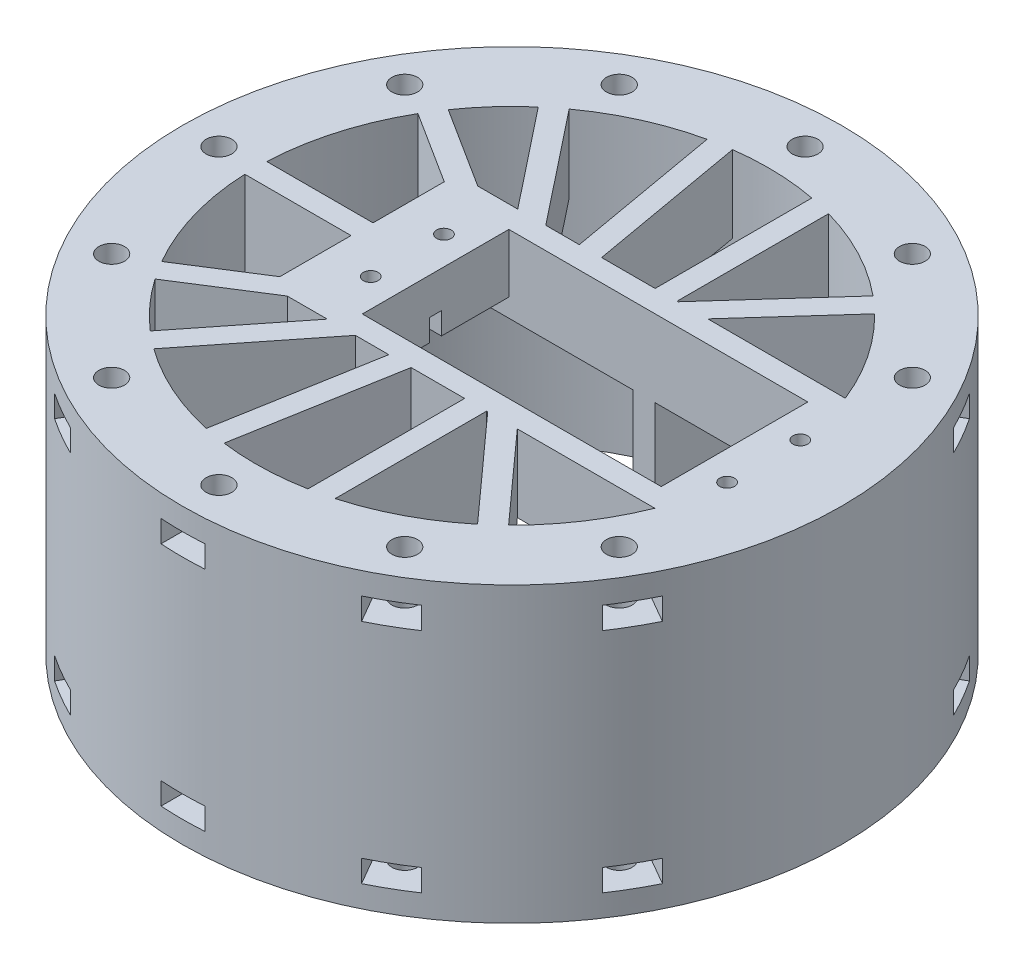
SolidWorks part; units mm, degrees
ref_plane "Front Plane" through (0, 0, 0) normal (0, 0, 1) x (1, 0, 0)
ref_plane "Top Plane" through (0, 0, 0) normal (0, 1, 0) x (1, 0, 0)
ref_plane "Right Plane" through (0, 0, 0) normal (1, 0, 0) x (0, 0, -1)
sketch "Sketch1" plane through (0, 0, 0) normal (0, 1, 0) x (1, 0, 0)
  line L0 (-43.0464, 0) -> (41.9462, 0) construction
  line L1 (0, 43.1152) -> (0, -41.8775) construction
  circle A1 centre (0, 0) radius 45
  dimension "D2" = 90
extrude "Boss-Extrude1" add sketch "Sketch1" along normal blind 40
sketch "Sketch2" plane through (0, 0, 0) normal (0, -1, 0) x (1, 0, 0)
  circle A0 centre (0, 0) radius 35
  dimension "D1" = 70
extrude "Cut-Extrude1" cut sketch "Sketch2" against normal blind 29.5
sketch "Sketch3" plane through (0, 29.5, 0) normal (0, -1, 0) x (1, 0, 0)
  line L0 (35, 0) -> (-35, 0) construction
  line L1 (0, -35) -> (0, 35) construction
  line L3 (37.5324, -10) -> (-17.4676, -10)
  line L4 (37.5324, -10) -> (37.5324, 10)
  line L5 (37.5324, 10) -> (-17.4676, 10)
  line L6 (-17.4676, -10) -> (-17.4676, 10)
  circle A0 centre (0, 0) radius 35 construction
  circle A1 centre (0, 0) radius 35 construction
  dimension "D1" = 20
  dimension "D2" = 55
  dimension "D3" = 10
  dimension "D4" = 37.5324
extrude "Cut-Extrude2" cut sketch "Sketch3" against normal blind 2.5 and the other way up to next
sketch "Sketch4" plane through (0, 32, 0) normal (0, -1, 0) x (1, 0, 0)
  line L0 (37.5324, 0) -> (-17.4676, 0) construction
  line L1 (37.5324, 10) -> (37.5324, -10) construction
  line L2 (-17.4676, 10) -> (-17.4676, -10) construction
  line L3 (0, -10) -> (0, 10) construction
  line L4 (-17.4676, -10) -> (33.541, -10) construction
  line L5 (33.541, 10) -> (-17.4676, 10) construction
  line L7 (30.3722, -10) -> (-10.4278, -10)
  line L8 (30.3722, -10) -> (30.3722, 10)
  line L9 (30.3722, 10) -> (-10.4278, 10)
  line L10 (-10.4278, -10) -> (-10.4278, 10)
  dimension "D1" = 20
  dimension "D2" = 40.8
  dimension "D3" = 30.3722
  dimension "D4" = 10
extrude "Cut-Extrude3" cut sketch "Sketch4" against normal blind 9
sketch "Sketch8" plane through (0, 29.5, 0) normal (0, -1, 0) x (1, 0, 0)
  line L0 (-17.4676, 0) -> (-35, 0) construction
  line L1 (-17.4676, 10) -> (-17.4676, -10) construction
  line L2 (8.0367, 10) -> (8.0367, 34.0648) construction
  line L3 (33.541, 10) -> (-17.4676, 10) construction
  line L4 (8.0367, -10) -> (8.0367, -29.3194) construction
  line L5 (-17.4676, -10) -> (33.541, -10) construction
  line L6 (6.5367, 10) -> (6.5367, 34.3842)
  line L7 (9.5367, 10) -> (9.5367, 33.6757)
  line L8 (9.5367, 10) -> (6.5367, 10)
  line L9 (9.5367, -10) -> (6.5367, -10)
  line L10 (6.5367, -10) -> (6.5367, -34.3842)
  line L11 (9.5367, -10) -> (9.5367, -33.6757)
  line L12 (-17.4676, 1.5) -> (-34.9678, 1.5)
  line L13 (-17.4676, -1.5) -> (-34.9678, -1.5)
  line L14 (-17.4676, 1.5) -> (-17.4676, -1.5)
  arc A0 (33.541, 10) -> (33.541, -10) centre (0, 0) ccw construction
  arc A1 (9.5367, 33.6757) -> (6.5367, 34.3842) centre (7.9531, 33.6757) ccw
  arc A2 (9.5367, -33.6757) -> (6.5367, -34.3842) centre (7.9531, -33.6757) cw
  arc A3 (-34.9678, 1.5) -> (-34.9678, -1.5) centre (-34.9678, 0) ccw
  dimension "D3" = 1.5
  dimension "D1" = 1.5
  dimension "D2" = 1.5
  dimension "D4" = 1.5
extrude "Boss-Extrude2" add sketch "Sketch8" along normal through all
sketch "Sketch16" plane through (0, 32, 0) normal (0, -1, 0) x (1, 0, 0)
  line L0 (-17.4676, 0) -> (37.5324, 0) construction
  line L1 (-17.4676, 10) -> (-17.4676, -10) construction
  line L2 (37.5324, -10) -> (37.5324, 10) construction
  line L3 (30.3722, -0.8) -> (37.5324, -0.8)
  line L4 (-10.4278, -0.8) -> (-17.4676, -0.8)
  line L5 (-10.4278, 10) -> (-10.4278, -10) construction
  line L6 (-10.4278, 0.8) -> (-17.4676, 0.8)
  line L7 (-17.4676, 0.8) -> (-17.4676, -0.8)
  line L8 (-10.4278, 0.8) -> (-10.4278, -0.8)
  line L9 (30.3722, -10) -> (30.3722, 10) construction
  line L10 (30.3722, 0.8) -> (37.5324, 0.8)
  line L11 (37.5324, 0.8) -> (37.5324, -0.8)
  line L12 (30.3722, 0.8) -> (30.3722, -0.8)
  dimension "D1" = 0.8
extrude "Cut-Extrude10" cut sketch "Sketch16" against normal blind 3
sketch "Sketch27" plane through (0, 0, 0) normal (0, -1, 0) x (1, 0, 0)
  line L0 (0, 0) -> (0, -53.17) construction
  line L1 (0, 0) -> (47.7582, -27.5732) construction
  line L3 (31.641, -18.2679) -> (31.641, -21.7321) construction
  line L4 (31.641, -21.7321) -> (34.641, -23.4641) construction
  line L5 (34.641, -23.4641) -> (37.641, -21.7321) construction
  line L6 (37.641, -21.7321) -> (37.641, -18.2679) construction
  line L7 (37.641, -18.2679) -> (34.641, -16.5359) construction
  line L8 (34.641, -16.5359) -> (31.641, -18.2679) construction
  circle A0 centre (0, 0) radius 40 construction
  circle A1 centre (34.641, -20) radius 1.75
  circle A2 centre (0, 0) radius 35 construction
  circle A3 centre (34.641, -20) radius 3 construction
  circle A4 centre (20, -34.641) radius 1.75
  circle A5 centre (0, -40) radius 1.75
  circle A6 centre (-20, -34.641) radius 1.75
  circle A7 centre (-34.641, -20) radius 1.75
  circle A8 centre (-40, 0) radius 1.75
  circle A9 centre (-34.641, 20) radius 1.75
  circle A10 centre (-20, 34.641) radius 1.75
  circle A11 centre (0, 40) radius 1.75
  circle A12 centre (20, 34.641) radius 1.75
  circle A13 centre (34.641, 20) radius 1.75
  circle A15 centre (40, 0) radius 1.75 [skipped]
  point P28 (0, 0)
  point P41 (0, 0)
  dimension "D1" = 80
  dimension "D3" = 3.5
  dimension "D4" = 70
  dimension "D5" = 6
  dimension "D6" = 12
  dimension "D2" = 60
extrude "Cut-Extrude15" cut sketch "Sketch27" against normal through all
ref_plane "Plane1" through (0, 37, 0) normal (0, 1, 0) x (1, 0, 0)
sketch "Sketch28" plane through (0, 37, 0) normal (0, 1, 0) x (1, 0, 0)
  line L0 (0, 0) -> (-54.493, 0) construction
  line L1 (-31.641, 18.2679) -> (-31.641, 21.7321)
  line L2 (-36.5359, 0) -> (-38.2679, 3)
  line L3 (-38.2679, 3) -> (-44.8999, 3)
  line L4 (-31.641, 21.7321) -> (-37.3844, 25.048)
  line L5 (-40.3844, 19.8519) -> (-34.641, 16.5359)
  line L6 (-44.8999, -3) -> (-38.2679, -3)
  line L7 (-38.2679, -3) -> (-36.5359, 0)
  line L8 (-43.4641, 0) -> (-42.5981, -1.5) [skipped]
  line L9 (-41.7321, 3) -> (-42.5981, 1.5) [skipped]
  line L10 (-34.641, 16.5359) -> (-31.641, 18.2679)
  line L11 (-18.2679, 31.641) -> (-16.5359, 34.641)
  line L12 (-16.5359, 34.641) -> (-19.8519, 40.3844)
  line L13 (-25.048, 37.3844) -> (-21.7321, 31.641)
  line L14 (-21.7321, 31.641) -> (-18.2679, 31.641)
  line L15 (0, 36.5359) -> (3, 38.2679)
  line L16 (3, 38.2679) -> (3, 44.8999)
  line L17 (-3, 44.8999) -> (-3, 38.2679)
  line L18 (-3, 38.2679) -> (0, 36.5359)
  line L19 (18.2679, 31.641) -> (21.7321, 31.641)
  line L20 (21.7321, 31.641) -> (25.048, 37.3844)
  line L21 (19.8519, 40.3844) -> (16.5359, 34.641)
  line L22 (16.5359, 34.641) -> (18.2679, 31.641)
  line L23 (31.641, 18.2679) -> (34.641, 16.5359)
  line L24 (34.641, 16.5359) -> (40.3844, 19.8519)
  line L25 (37.3844, 25.048) -> (31.641, 21.7321)
  line L26 (31.641, 21.7321) -> (31.641, 18.2679)
  line L31 (31.641, -18.2679) -> (31.641, -21.7321)
  line L32 (31.641, -21.7321) -> (37.3844, -25.048)
  line L33 (40.3844, -19.8519) -> (34.641, -16.5359)
  line L34 (34.641, -16.5359) -> (31.641, -18.2679)
  line L35 (18.2679, -31.641) -> (16.5359, -34.641)
  line L36 (16.5359, -34.641) -> (19.8519, -40.3844)
  line L37 (25.048, -37.3844) -> (21.7321, -31.641)
  line L38 (21.7321, -31.641) -> (18.2679, -31.641)
  line L39 (0, -36.5359) -> (-3, -38.2679)
  line L40 (-3, -38.2679) -> (-3, -44.8999)
  line L41 (3, -44.8999) -> (3, -38.2679)
  line L42 (3, -38.2679) -> (0, -36.5359)
  line L43 (-18.2679, -31.641) -> (-21.7321, -31.641)
  line L44 (-21.7321, -31.641) -> (-25.048, -37.3844)
  line L45 (-19.8519, -40.3844) -> (-16.5359, -34.641)
  line L46 (-16.5359, -34.641) -> (-18.2679, -31.641)
  line L47 (-31.641, -18.2679) -> (-34.641, -16.5359)
  line L48 (-34.641, -16.5359) -> (-40.3844, -19.8519)
  line L49 (-37.3844, -25.048) -> (-31.641, -21.7321)
  line L50 (-31.641, -21.7321) -> (-31.641, -18.2679)
  line L51 (36.5359, 0) -> (38.2679, -3) [skipped]
  line L52 (38.2679, -3) -> (44.8999, -3) [skipped]
  line L53 (44.8999, 3) -> (38.2679, 3) [skipped]
  line L54 (38.2679, 3) -> (36.5359, 0) [skipped]
  arc A0 (-44.8999, 3) -> (-44.8999, -3) centre (0, 0) ccw
  circle A1 centre (-40, 0) radius 3 construction
  arc A2 (-37.3844, 25.048) -> (-40.3844, 19.8519) centre (0, 0) ccw
  circle A3 centre (-34.641, 20) radius 3 construction
  arc A4 (-19.8519, 40.3844) -> (-25.048, 37.3844) centre (0, 0) ccw
  circle A5 centre (-20, 34.641) radius 3 construction
  arc A6 (3, 44.8999) -> (-3, 44.8999) centre (0, 0) ccw
  circle A7 centre (0, 40) radius 3 construction
  arc A8 (25.048, 37.3844) -> (19.8519, 40.3844) centre (0, 0) ccw
  circle A9 centre (20, 34.641) radius 3 construction
  arc A10 (40.3844, 19.8519) -> (37.3844, 25.048) centre (0, 0) ccw
  circle A11 centre (34.641, 20) radius 3 construction
  arc A14 (37.3844, -25.048) -> (40.3844, -19.8519) centre (0, 0) ccw
  circle A15 centre (34.641, -20) radius 3 construction
  arc A16 (19.8519, -40.3844) -> (25.048, -37.3844) centre (0, 0) ccw
  circle A17 centre (20, -34.641) radius 3 construction
  arc A18 (-3, -44.8999) -> (3, -44.8999) centre (0, 0) ccw
  circle A19 centre (0, -40) radius 3 construction
  arc A20 (-25.048, -37.3844) -> (-19.8519, -40.3844) centre (0, 0) ccw
  circle A21 centre (-20, -34.641) radius 3 construction
  arc A22 (-40.3844, -19.8519) -> (-37.3844, -25.048) centre (0, 0) ccw
  circle A23 centre (-34.641, -20) radius 3 construction
  arc A24 (44.8999, -3) -> (44.8999, 3) centre (0, 0) ccw [skipped]
  circle A25 centre (40, 0) radius 3 construction
  point P94 (0, 0)
  dimension "D1" = 90
  dimension "D2" = 6
  dimension "D3" = 12
extrude "Cut-Extrude17" cut sketch "Sketch28" against normal blind 3
sketch "Sketch29" plane through (0, 29.5, 0) normal (0, -1, 0) x (1, 0, 0)
  line L0 (32.4962, -13) -> (13.7255, -13)
  line L1 (9.5367, -33.6757) -> (9.5367, -10) construction
  line L2 (9.5367, -13) -> (9.5367, -33.6757)
  line L3 (9.5367, -10) -> (33.541, -10) construction
  line L4 (6.5367, -13) -> (-0.7691, -13)
  line L5 (6.5367, -10) -> (6.5367, -34.3842) construction
  line L6 (-20.4676, -11.223) -> (-20.4676, -1.5)
  line L7 (-34.9678, -1.5) -> (-17.4676, -1.5) construction
  line L8 (-20.4676, -1.5) -> (-34.9678, -1.5)
  line L9 (-17.4676, -0.8) -> (-17.4676, -10) construction
  line L10 (32.4962, 13) -> (13.7255, 13)
  line L11 (9.5367, 10) -> (9.5367, 33.6757) construction
  line L12 (9.5367, 13) -> (9.5367, 33.6757)
  line L13 (-7.5493, 34.1761) -> (-3.8154, 13)
  line L14 (6.5367, 13) -> (-0.7691, 13)
  line L15 (6.5367, 34.3842) -> (6.5367, 10) construction
  line L16 (-20.4676, 11.223) -> (-20.4676, 1.5)
  line L17 (-17.4676, 1.5) -> (-34.9678, 1.5) construction
  line L18 (-20.4676, 1.5) -> (-34.9678, 1.5)
  line L19 (6.5367, 13) -> (6.5367, 34.3842)
  line L20 (6.5367, -34.3842) -> (6.5367, -13)
  line L21 (0, 0) -> (-21.7353, -27.4331) construction
  line L22 (-20.5397, -28.3394) -> (-8.3862, -13)
  line L23 (-22.8911, -26.4764) -> (-12.2137, -13)
  line L24 (0, 0) -> (-20.4676, -13) construction
  line L25 (-17.6698, -13) -> (-28.713, -20.0141)
  line L26 (-20.4676, -11.223) -> (-30.3215, -17.4817)
  line L27 (0, 0) -> (-35, 0) construction
  line L28 (-20.4676, 11.223) -> (-30.3215, 17.4817)
  line L29 (-17.6698, 13) -> (-28.713, 20.0141)
  line L30 (-22.8911, 26.4764) -> (-12.2137, 13)
  line L31 (-20.5397, 28.3394) -> (-8.3862, 13)
  line L32 (-12.2137, 13) -> (-17.6698, 13)
  line L33 (0, 0) -> (-6.0777, -34.4683) construction
  line L34 (-4.5949, -34.6971) -> (-0.7691, -13)
  line L35 (-7.5493, -34.1761) -> (-3.8154, -13)
  line L36 (-3.8154, -13) -> (-17.6698, -13)
  line L37 (-4.5949, 34.6971) -> (-0.7691, 13)
  line L38 (-3.8154, 13) -> (-8.3862, 13)
  line L39 (0, 0) -> (23.4214, -26.0084) construction
  line L40 (9.6883, -13) -> (22.2852, -26.9883)
  line L41 (13.7255, -13) -> (24.5145, -24.9808)
  line L42 (13.7255, 13) -> (24.5145, 24.9808)
  line L43 (9.6883, 13) -> (22.2852, 26.9883)
  line L44 (9.6883, -13) -> (9.5367, -13)
  line L45 (9.6883, 13) -> (9.5367, 13)
  arc A0 (9.5367, -33.6757) -> (22.2852, -26.9883) centre (0, 0) ccw
  arc A1 (6.5367, 34.3842) -> (-4.5949, 34.6971) centre (0, 0) ccw
  arc A2 (32.4962, 13) -> (24.5145, 24.9808) centre (0, 0) ccw
  arc A3 (-34.9678, -1.5) -> (-30.3215, -17.4817) centre (0, 0) ccw
  circle A4 centre (0, 0) radius 35 construction
  arc A5 (-7.5493, 34.1761) -> (-20.5397, 28.3394) centre (0, 0) ccw
  arc A6 (-4.5949, -34.6971) -> (6.5367, -34.3842) centre (0, 0) ccw
  arc A7 (-20.5397, -28.3394) -> (-7.5493, -34.1761) centre (0, 0) ccw
  arc A8 (-28.713, -20.0141) -> (-22.8911, -26.4764) centre (0, 0) ccw
  arc A9 (-30.3215, 17.4817) -> (-34.9678, 1.5) centre (0, 0) ccw
  arc A10 (-22.8911, 26.4764) -> (-28.713, 20.0141) centre (0, 0) ccw
  arc A11 (24.5145, -24.9808) -> (32.4962, -13) centre (0, 0) ccw
  arc A12 (22.2852, 26.9883) -> (9.5367, 33.6757) centre (0, 0) ccw
  point P11 (21.5389, -10)
  point P23 (-17.4676, -5.4)
  line M3 (-17.4676, -1.5) -> (-34.9678, -1.5)
  arc M4 (-34.9678, -1.5) -> (6.5367, -34.3842) centre (0, 0) ccw
  line M5 (6.5367, -34.3842) -> (6.5367, -10)
  dimension "D1" = 1.5
  dimension "D2" = 3
  dimension "D3" = 3
  dimension "D4" = 80
  dimension "D5" = 1.5
  dimension "D6" = 1.5
  dimension "D7" = 1.5
sketch "Sketch32" plane through (0, 32, 0) normal (0, -1, 0) x (1, 0, 0)
  line L0 (-17.4676, 0) -> (37.5324, 0) construction
  line L1 (-17.4676, -1.5) -> (-17.4676, 1.5) construction
  line L2 (37.5324, 10) -> (37.5324, -10) construction
  line L3 (10.0324, 0) -> (10.0324, -10) construction
  line L6 (9.5367, -10) -> (33.541, -10) construction
  circle A0 centre (-14.2876, -5) radius 1
  circle A1 centre (-14.2876, 5) radius 1
  circle A2 centre (34.3524, -5) radius 1
  circle A3 centre (34.3524, 5) radius 1
  dimension "D1" = 24.32
  dimension "D3" = 2
  dimension "D2" = 5
extrude "Cut-Extrude21" cut sketch "Sketch32" against normal through all
extrude "Cut-Extrude22" cut sketch "Sketch29" against normal blind 12 contours L28 A9 L18 L16 | L26 L6 M3 M4 | L23 L36 L25 M4 | L35 L36 L22 M4 | L34 L4 M4 M5 | L2 A0 L40 L44 | L41 A11 L0 | L10 A2 L42 | L43 A12 L12 L45 | L19 A1 L37 L14 | L13 A5 L31 L38 | L30 A10 L29 L32
sketch "Sketch33" plane through (0, 0, 1.5) normal (0, 0, 1) x (1, 0, 0)
  line L0 (-17.4676, 14.75) -> (-34.9678, 0)
  line L1 (-17.4676, 0) -> (-17.4676, 29.5) construction
  line L2 (-34.9678, 0) -> (-17.4676, 0)
  line L3 (-17.4676, 0) -> (-34.9678, 0) construction
  line L4 (-17.4676, 0) -> (-17.4676, 14.75)
extrude "Cut-Extrude23" cut sketch "Sketch33" against normal up to next
ref_plane "Plane2" through (0, 3, 0) normal (0, -1, 0) x (-1, 0, 0)
sketch "Sketch34" plane through (0, 3, 0) normal (0, -1, 0) x (-1, 0, 0)
  line L0 (0, 0) -> (0, 45) construction
  line L1 (18.2679, 31.641) -> (21.7321, 31.641)
  line L2 (0, 36.5359) -> (3, 38.2679)
  line L3 (3, 38.2679) -> (3, 44.8999)
  line L4 (21.7321, 31.641) -> (25.048, 37.3844)
  line L5 (19.8519, 40.3844) -> (16.5359, 34.641)
  line L6 (-3, 44.8999) -> (-3, 38.2679)
  line L7 (-3, 38.2679) -> (0, 36.5359)
  line L8 (0, 43.4641) -> (-1.5, 42.5981) [skipped]
  line L9 (3, 41.7321) -> (1.5, 42.5981) [skipped]
  line L10 (16.5359, 34.641) -> (18.2679, 31.641)
  line L11 (31.641, 18.2679) -> (34.641, 16.5359)
  line L12 (34.641, 16.5359) -> (40.3844, 19.8519)
  line L13 (37.3844, 25.048) -> (31.641, 21.7321)
  line L14 (31.641, 21.7321) -> (31.641, 18.2679)
  line L15 (36.5359, 0) -> (38.2679, -3)
  line L16 (38.2679, -3) -> (44.8999, -3)
  line L17 (44.8999, 3) -> (38.2679, 3)
  line L18 (38.2679, 3) -> (36.5359, 0)
  line L19 (31.641, -18.2679) -> (31.641, -21.7321)
  line L20 (31.641, -21.7321) -> (37.3844, -25.048)
  line L21 (40.3844, -19.8519) -> (34.641, -16.5359)
  line L22 (34.641, -16.5359) -> (31.641, -18.2679)
  line L23 (18.2679, -31.641) -> (16.5359, -34.641)
  line L24 (16.5359, -34.641) -> (19.8519, -40.3844)
  line L25 (25.048, -37.3844) -> (21.7321, -31.641)
  line L26 (21.7321, -31.641) -> (18.2679, -31.641)
  line L27 (0, -36.5359) -> (-3, -38.2679)
  line L28 (-3, -38.2679) -> (-3, -44.8999)
  line L29 (3, -44.8999) -> (3, -38.2679)
  line L30 (3, -38.2679) -> (0, -36.5359)
  line L31 (-18.2679, -31.641) -> (-21.7321, -31.641)
  line L32 (-21.7321, -31.641) -> (-25.048, -37.3844)
  line L33 (-19.8519, -40.3844) -> (-16.5359, -34.641)
  line L34 (-16.5359, -34.641) -> (-18.2679, -31.641)
  line L35 (-31.641, -18.2679) -> (-34.641, -16.5359)
  line L36 (-34.641, -16.5359) -> (-40.3844, -19.8519)
  line L37 (-37.3844, -25.048) -> (-31.641, -21.7321)
  line L38 (-31.641, -21.7321) -> (-31.641, -18.2679)
  line L43 (-31.641, 18.2679) -> (-31.641, 21.7321)
  line L44 (-31.641, 21.7321) -> (-37.3844, 25.048)
  line L45 (-40.3844, 19.8519) -> (-34.641, 16.5359)
  line L46 (-34.641, 16.5359) -> (-31.641, 18.2679)
  line L47 (-18.2679, 31.641) -> (-16.5359, 34.641)
  line L48 (-16.5359, 34.641) -> (-19.8519, 40.3844)
  line L49 (-25.048, 37.3844) -> (-21.7321, 31.641)
  line L50 (-21.7321, 31.641) -> (-18.2679, 31.641)
  line L51 (-36.5359, 0) -> (-38.2679, 3) [skipped]
  line L52 (-38.2679, 3) -> (-44.8999, 3) [skipped]
  line L53 (-44.8999, -3) -> (-38.2679, -3) [skipped]
  line L54 (-38.2679, -3) -> (-36.5359, 0) [skipped]
  circle A0 centre (0, 0) radius 45 construction
  circle A1 centre (0, 40) radius 3 construction
  arc A2 (3, 44.8999) -> (-3, 44.8999) centre (0, 0) ccw
  arc A3 (25.048, 37.3844) -> (19.8519, 40.3844) centre (0, 0) ccw
  circle A4 centre (20, 34.641) radius 3 construction
  arc A5 (40.3844, 19.8519) -> (37.3844, 25.048) centre (0, 0) ccw
  circle A6 centre (34.641, 20) radius 3 construction
  arc A7 (44.8999, -3) -> (44.8999, 3) centre (0, 0) ccw
  circle A8 centre (40, 0) radius 3 construction
  arc A9 (37.3844, -25.048) -> (40.3844, -19.8519) centre (0, 0) ccw
  circle A10 centre (34.641, -20) radius 3 construction
  arc A11 (19.8519, -40.3844) -> (25.048, -37.3844) centre (0, 0) ccw
  circle A12 centre (20, -34.641) radius 3 construction
  arc A13 (-3, -44.8999) -> (3, -44.8999) centre (0, 0) ccw
  circle A14 centre (0, -40) radius 3 construction
  arc A15 (-25.048, -37.3844) -> (-19.8519, -40.3844) centre (0, 0) ccw
  circle A16 centre (-20, -34.641) radius 3 construction
  arc A17 (-40.3844, -19.8519) -> (-37.3844, -25.048) centre (0, 0) ccw
  circle A18 centre (-34.641, -20) radius 3 construction
  arc A21 (-37.3844, 25.048) -> (-40.3844, 19.8519) centre (0, 0) ccw
  circle A22 centre (-34.641, 20) radius 3 construction
  arc A23 (-19.8519, 40.3844) -> (-25.048, 37.3844) centre (0, 0) ccw
  circle A24 centre (-20, 34.641) radius 3 construction
  arc A25 (-44.8999, 3) -> (-44.8999, -3) centre (0, 0) ccw [skipped]
  circle A26 centre (-40, 0) radius 3 construction
  point P98 (0, 0)
  dimension "D1" = 6
  dimension "D2" = 90
  dimension "D3" = 12
extrude "Cut-Extrude24" cut sketch "Sketch34" against normal blind 3
